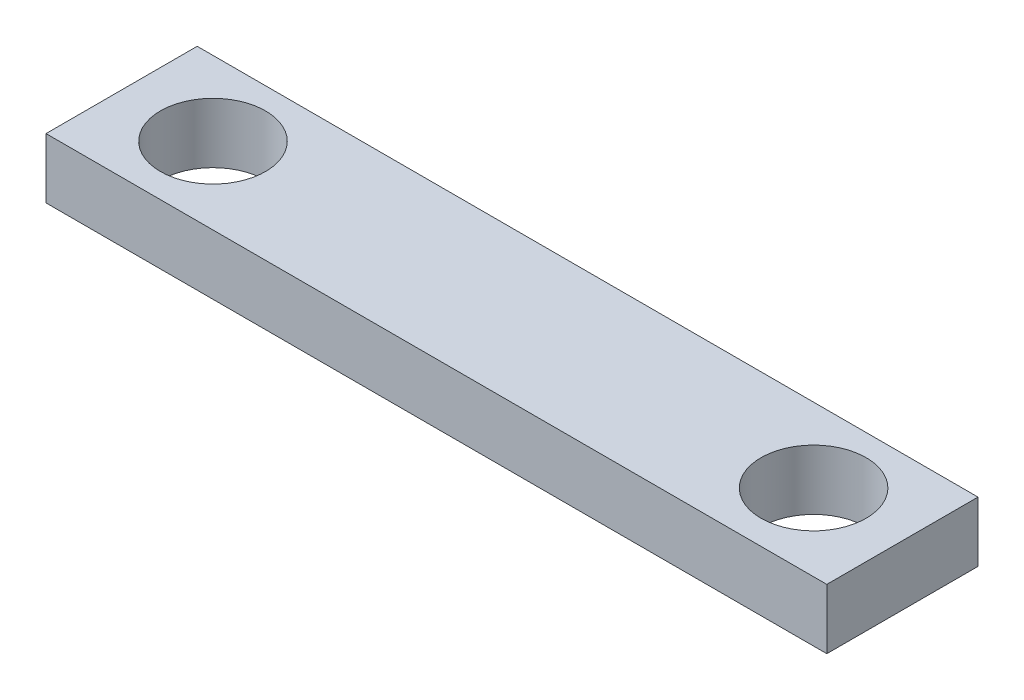
SolidWorks part; units mm, degrees
ref_plane "前视基准面" through (0, 0, 0) normal (0, 0, 1) x (1, 0, 0)
ref_plane "上视基准面" through (0, 0, 0) normal (0, 1, 0) x (1, 0, 0)
ref_plane "右视基准面" through (0, 0, 0) normal (1, 0, 0) x (0, 0, -1)
other "Configuration Table"
sketch "草图1" plane through (0, 0, 0) normal (0, 1, 0) x (1, 0, 0)
  line L1 (-8.6188, 2.8587) -> (17.3812, 2.8587)
  line L2 (-8.6188, 2.8587) -> (-8.6188, -2.176)
  line L3 (-8.6188, -2.176) -> (17.3812, -2.176)
  line L4 (17.3812, 2.8587) -> (17.3812, -2.176)
  circle A0 centre (-5.6188, 0.384) radius 1.75
  circle A1 centre (14.3812, 0.384) radius 1.75
  dimension "D1" = 3.5
  dimension "D2" = 3.5
  dimension "D3" = 3
  dimension "D4" = 3
  dimension "D5" = 20
extrude "凸台-拉伸1" add sketch "草图1" along normal blind 2
